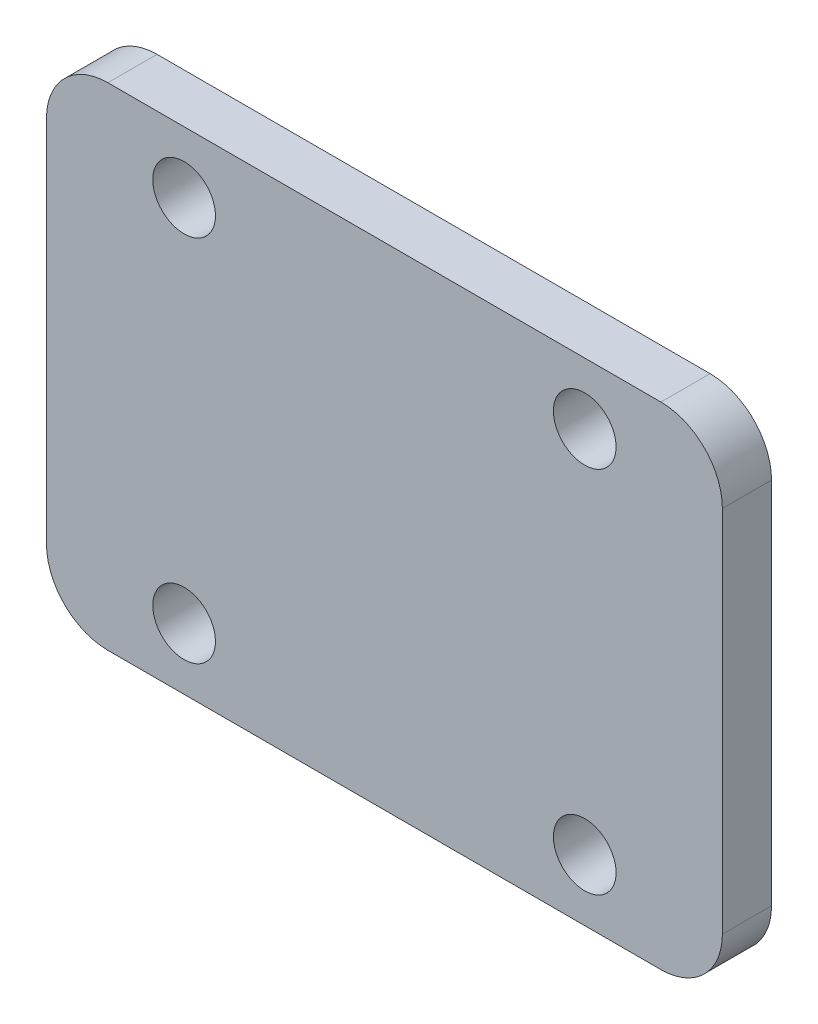
SolidWorks part; units mm, degrees
material "Plain Carbon Steel"
ref_plane "Front Plane" through (0, 0, 0) normal (0, 0, 1) x (1, 0, 0)
ref_plane "Top Plane" through (0, 0, 0) normal (0, 1, 0) x (1, 0, 0)
ref_plane "Right Plane" through (0, 0, 0) normal (1, 0, 0) x (0, 0, -1)
sketch "Sketch2" plane through (0, 0, 0) normal (0, 0, 1) x (1, 0, 0)
  line L0 (0, 22.2023) -> (0, -24.5224) construction
  line L1 (-22.5, -20) -> (22.5, -20)
  line L2 (-27.5, -15) -> (-27.5, 15)
  line L3 (-22.5, 20) -> (22.5, 20)
  line L4 (27.5, -15) -> (27.5, 15)
  line L5 (-27.5, -20) -> (27.5, 20) construction
  line L6 (-27.5, 20) -> (27.5, -20) construction
  line L7 (-49.5281, 0) -> (50.6882, 0) construction
  line L8 (-16.3, 24.2646) -> (-16.3, -25.7469) construction
  circle A0 centre (-16.3, 15) radius 2.55
  circle A1 centre (-16.3, -15) radius 2.55
  circle A2 centre (16.3, -15) radius 2.55
  circle A3 centre (16.3, 15) radius 2.55
  arc A4 (-22.5, -20) -> (-27.5, -15) centre (-22.5, -15) cw
  arc A5 (22.5, -20) -> (27.5, -15) centre (22.5, -15) ccw
  arc A6 (22.5, 20) -> (27.5, 15) centre (22.5, 15) cw
  arc A7 (-27.5, 15) -> (-22.5, 20) centre (-22.5, 15) cw
  point P0 (0, 0)
  dimension "D4" = 5.1
  dimension "D6" = 5
  dimension "D1" = 16.3
  dimension "D2" = 55
  dimension "D3" = 40
  dimension "D5" = 15
extrude "Boss-Extrude1" add sketch "Sketch2" along normal blind 4
